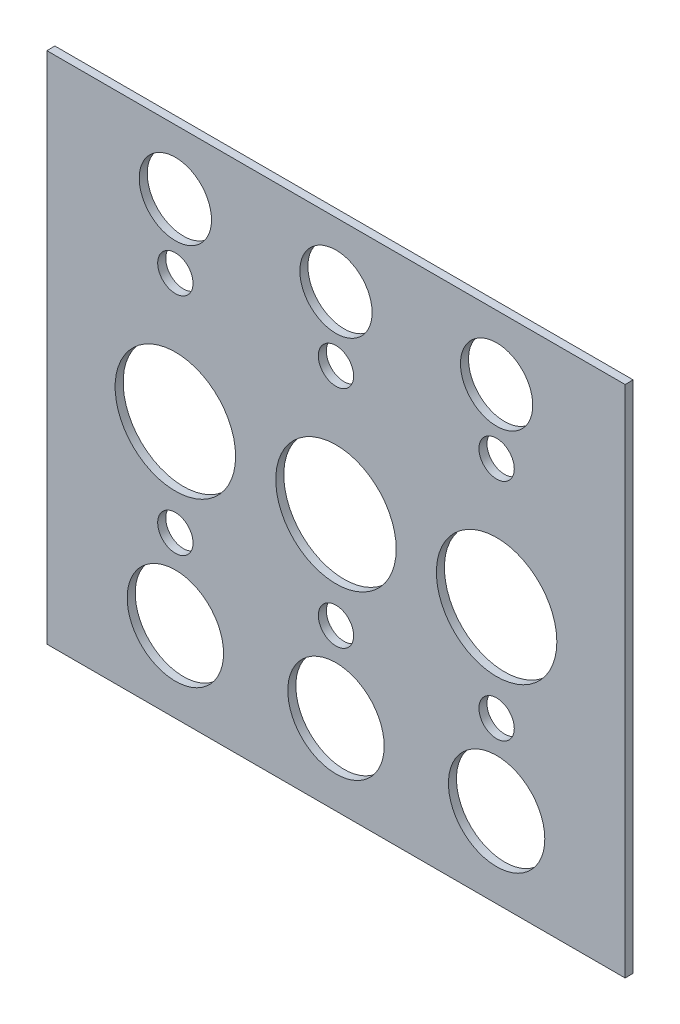
SolidWorks part; units mm, degrees
ref_plane "Plano frontal" through (0, 0, 0) normal (0, 0, 1) x (1, 0, 0)
ref_plane "Plano superior" through (0, 0, 0) normal (0, 1, 0) x (1, 0, 0)
ref_plane "Plano direito" through (0, 0, 0) normal (1, 0, 0) x (0, 0, -1)
sketch "Esboço1" plane through (0, 0, 0) normal (0, 0, 1) x (1, 0, 0)
  line L0 (0, 110) -> (0, -110) construction
  line L1 (-180, 160) -> (180, 160)
  line L2 (-180, 160) -> (-180, -160)
  line L3 (-180, -160) -> (180, -160)
  line L4 (180, 160) -> (180, -160)
  line L5 (-180, 160) -> (180, -160) construction
  line L6 (-180, -160) -> (180, 160) construction
  line L7 (-130, -110) -> (130, -110) construction
  line L8 (-130, -110) -> (-130, 110) construction
  line L9 (-130, 110) -> (130, 110) construction
  line L10 (130, -110) -> (130, 110) construction
  line L11 (-130, -110) -> (130, 110) construction
  line L12 (-130, 110) -> (130, -110) construction
  line L13 (180, 80) -> (-180, 80) construction
  line L14 (180, -60) -> (-180, -60) construction
  line L15 (-100, 160) -> (-100, -160) construction
  line L16 (100, 160) -> (100, -160) construction
  line L17 (-100, 160) -> (-100, 80) construction
  line L18 (-100, 120) -> (100, 120) construction
  circle A0 centre (0, 80) radius 11
  circle A1 centre (-100, 80) radius 11
  circle A2 centre (100, 80) radius 11
  circle A3 centre (0, -60) radius 11
  circle A4 centre (100, -60) radius 11
  circle A5 centre (-100, -60) radius 11
  circle A6 centre (-100, 0) radius 37.5
  circle A7 centre (0, 0) radius 37.5
  circle A8 centre (100, 0) radius 37.5
  circle A9 centre (100, -110) radius 30
  circle A10 centre (0, -110) radius 30
  circle A11 centre (-100, -110) radius 30
  circle A12 centre (-100, 120) radius 22.5
  circle A13 centre (0, 120) radius 22.5
  circle A14 centre (100, 120) radius 22.5
  point P0 (0, 0)
  point P6 (0, 0)
  point P44 (0, 120)
  point P52 (-100, 122.0548)
  point P53 (0, 0)
  dimension "D5" = 22
  dimension "D10" = 75
  dimension "D11" = 60
  dimension "D12" = 45
  dimension "D1" = 360
  dimension "D2" = 320
  dimension "D3" = 260
  dimension "D4" = 220
  dimension "D6" = 30
  dimension "D8" = 100
  dimension "D9" = 100
  dimension "D7" = 140
extrude "Ressalto-extrusão1" add sketch "Esboço1" along normal blind 5
